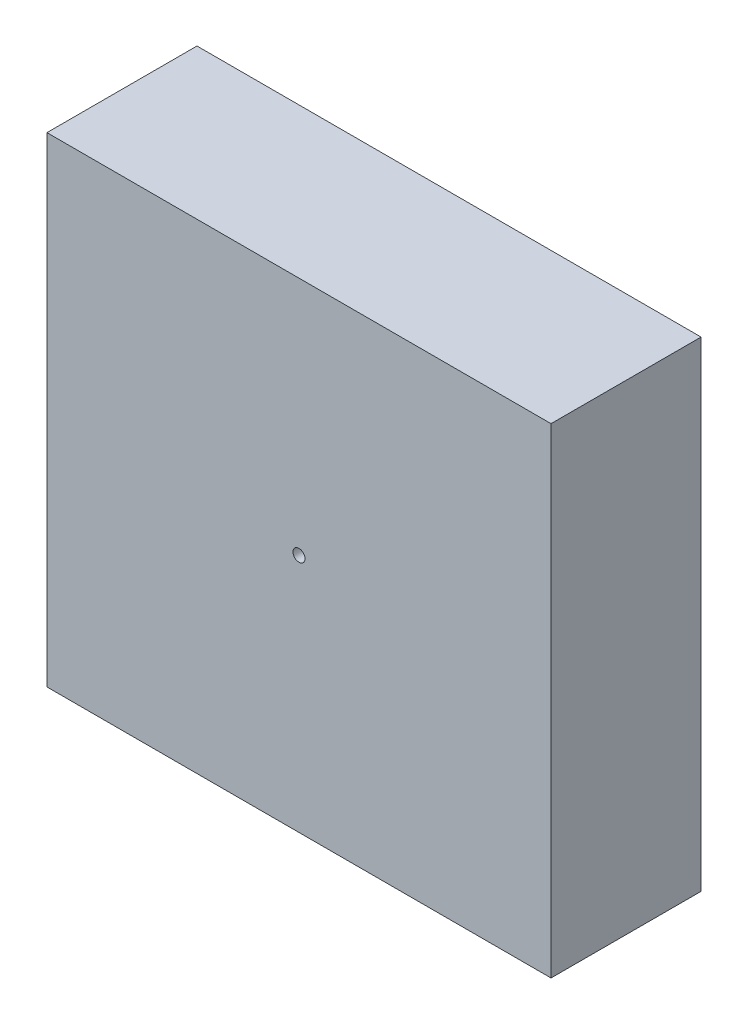
SolidWorks part; units mm, degrees
ref_plane "Alzado" through (0, 0, 0) normal (0, 0, 1) x (1, 0, 0)
ref_plane "Planta" through (0, 0, 0) normal (0, 1, 0) x (1, 0, 0)
ref_plane "Vista lateral" through (0, 0, 0) normal (1, 0, 0) x (0, 0, -1)
sketch "Croquis1" plane through (0, 0, 0) normal (0, 0, 1) x (1, 0, 0)
  line L1 (-42, 40) -> (42, 40)
  line L2 (-42, 40) -> (-42, -40)
  line L3 (-42, -40) -> (42, -40)
  line L4 (42, 40) -> (42, -40)
  line L5 (-42, 40) -> (42, -40) construction
  line L6 (-42, -40) -> (42, 40) construction
  point P0 (0, 0)
  dimension "D1" = 80
  dimension "D2" = 84
extrude "Saliente-Extruir1" add sketch "Croquis1" along normal blind 25
sketch "Croquis2" plane through (0, 0, 25) normal (0, 0, 1) x (1, 0, 0)
  circle A0 centre (0, 0) radius 1
extrude "Cortar-Extruir1" cut sketch "Croquis2" against normal blind 10
